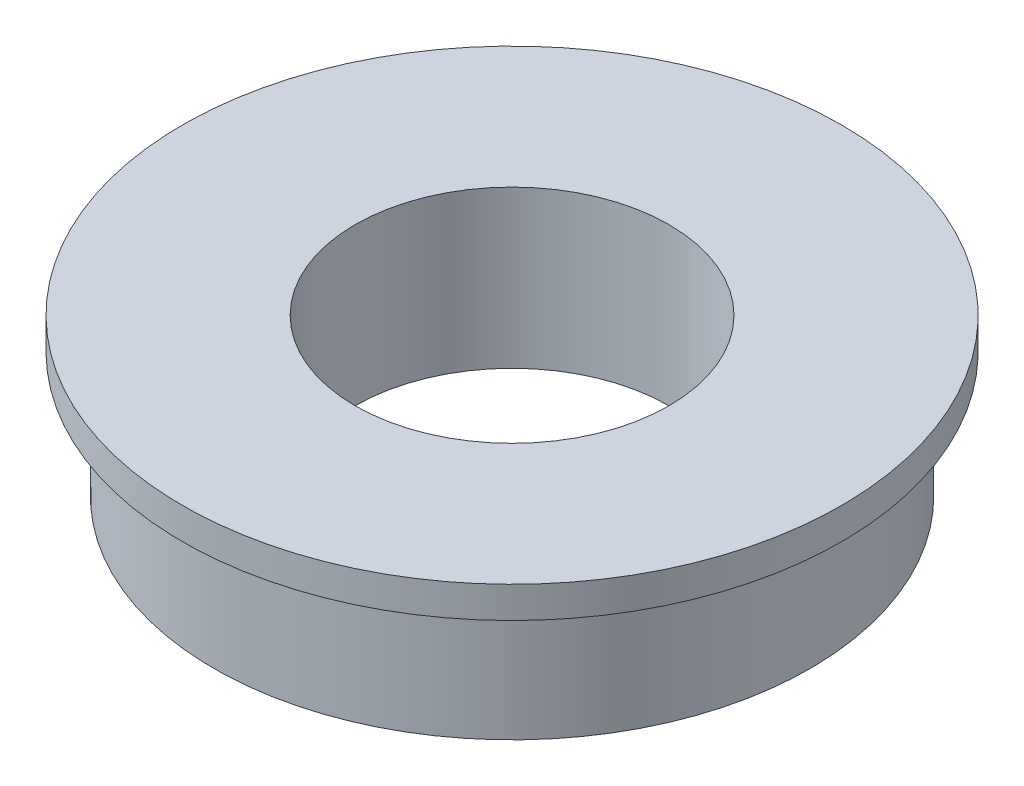
SolidWorks part; units mm, degrees
material "合金钢"
ref_plane "前视基准面" through (0, 0, 0) normal (0, 0, 1) x (1, 0, 0)
ref_plane "上视基准面" through (0, 0, 0) normal (0, 1, 0) x (1, 0, 0)
ref_plane "右视基准面" through (0, 0, 0) normal (1, 0, 0) x (0, 0, -1)
sketch "草图2" plane through (0, 0, 0) normal (0, 0, 1) x (1, 0, 0)
  line L0 (0, 0) -> (0, 5) construction
  line L1 (-5, 0) -> (-9.5, 0)
  line L2 (-9.5, 0) -> (-9.5, 4)
  line L3 (-9.5, 4) -> (-10.5, 4)
  line L4 (-10.5, 4) -> (-10.5, 5)
  line L5 (-10.5, 5) -> (-5, 5)
  line L6 (-5, 5) -> (-5, 0)
  dimension "D1" = 5
  dimension "D2" = 1
  dimension "D3" = 10.5
  dimension "D4" = 9.5
  dimension "D5" = 5
revolve "旋转1" add sketch "草图2" angle 360 about L0
